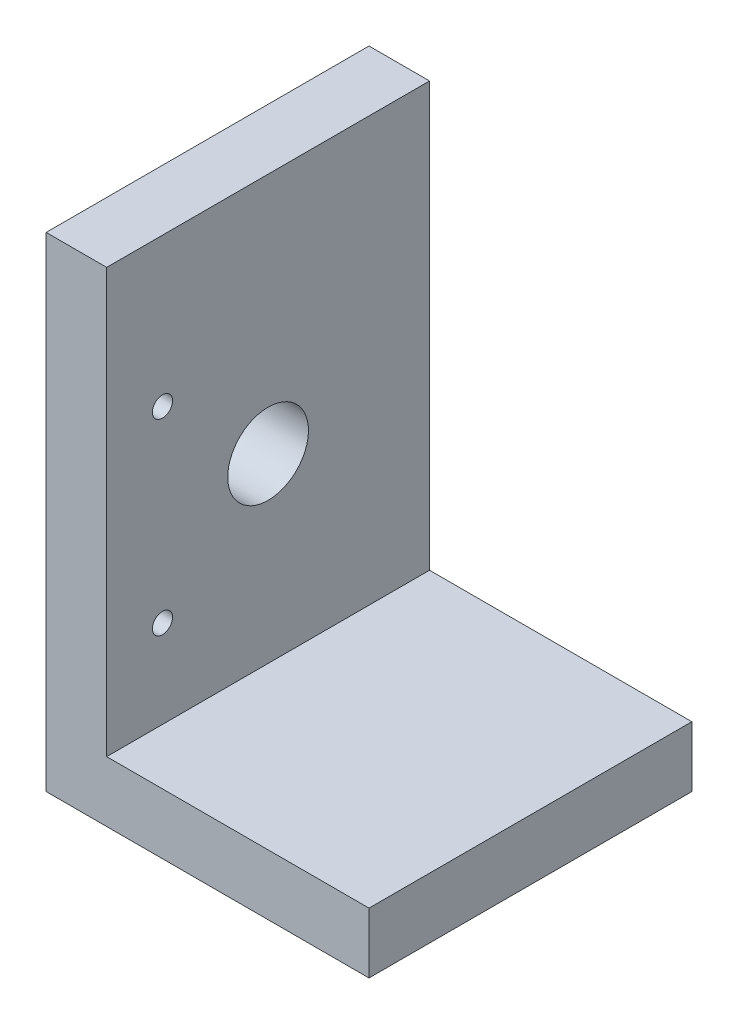
SolidWorks part; units mm, degrees
material "6061-T6 (SS)"
ref_plane "Front Plane" through (0, 0, 0) normal (0, 0, 1) x (1, 0, 0)
ref_plane "Top Plane" through (0, 0, 0) normal (0, 1, 0) x (1, 0, 0)
ref_plane "Right Plane" through (0, 0, 0) normal (1, 0, 0) x (0, 0, -1)
sketch "Sketch2" plane through (0, 0, 0) normal (0, 0, 1) x (1, 0, 0)
  line L0 (0, 0) -> (0, 76.2)
  line L1 (0, 76.2) -> (9.525, 76.2)
  line L2 (9.525, 76.2) -> (9.525, 9.525)
  line L3 (9.525, 9.525) -> (50.8, 9.525)
  line L4 (50.8, 9.525) -> (50.8, 0)
  line L5 (50.8, 0) -> (0, 0)
  dimension "D1" = 50.8
  dimension "D2" = 76.2
  dimension "D3" = 9.525
  dimension "D4" = 9.525
extrude "Boss-Extrude1" add sketch "Sketch2" along normal mid plane 50.8
sketch "Sketch3" plane through (9.525, 0, 0) normal (1, 0, 0) x (0, 0, -1)
  line L0 (0, 38.1) -> (0, 0) construction
  circle A0 centre (0, 38.1) radius 6.35
  dimension "D1" = 12.7
  dimension "D2" = 38.1
extrude "Cut-Extrude1" cut sketch "Sketch3" against normal through all
sketch "Sketch4" plane through (9.525, 0, 0) normal (1, 0, 0) x (0, 0, -1)
  line L0 (0, 38.1) -> (-17.6323, 51.6297) construction
  line L1 (0, 38.1) -> (-22.225, 38.1) construction
  line L2 (0, 38.1) -> (-17.6323, 24.5703) construction
  circle A0 centre (0, 38.1) radius 6.35 construction
  circle A1 centre (0, 38.1) radius 6.35 construction
  circle A2 centre (0, 38.1) radius 22.225 construction
  circle A3 centre (-16.6215, 52.8539) radius 1.5875
  circle A4 centre (-16.6215, 23.3461) radius 1.5875
  dimension "D1" = 44.45
  dimension "D4" = 3.175
  dimension "D5" = 3.175
  dimension "D2" = 37.5
  dimension "D3" = 37.5
extrude "Cut-Extrude2" cut sketch "Sketch4" against normal through all contours A3 | A4
